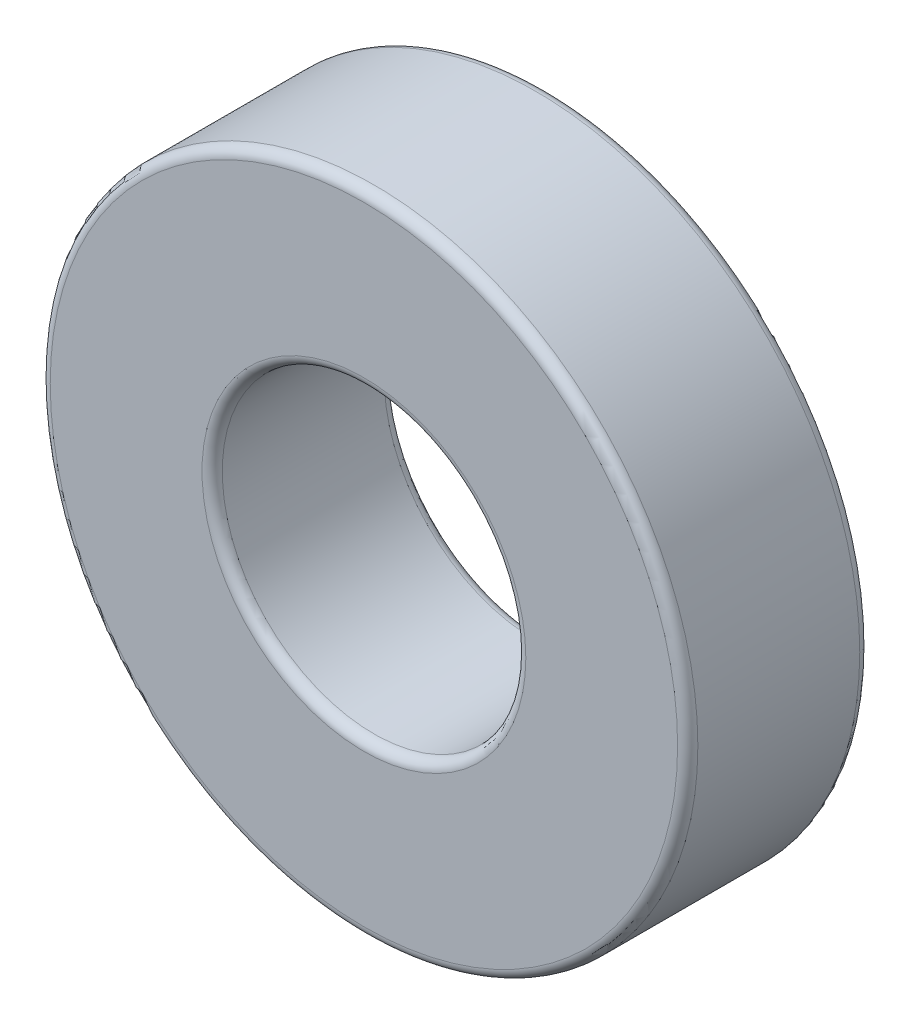
SolidWorks part; units mm, degrees
ref_plane "前视基准面" through (0, 0, 0) normal (0, 0, 1) x (1, 0, 0)
ref_plane "上视基准面" through (0, 0, 0) normal (0, 1, 0) x (1, 0, 0)
ref_plane "右视基准面" through (0, 0, 0) normal (1, 0, 0) x (0, 0, -1)
sketch "草图1" plane through (0, 0, 0) normal (0, 0, 1) x (1, 0, 0)
  circle A0 centre (0, 0) radius 16
  circle A1 centre (0, 0) radius 7.5
extrude "拉伸1" add sketch "草图1" along normal blind 9
fillet "圆角1" radius 0.5 4 edges at (16, 0, 0) (16, 0, 9) (7.5, 0, 9) (7.5, 0, 0)
